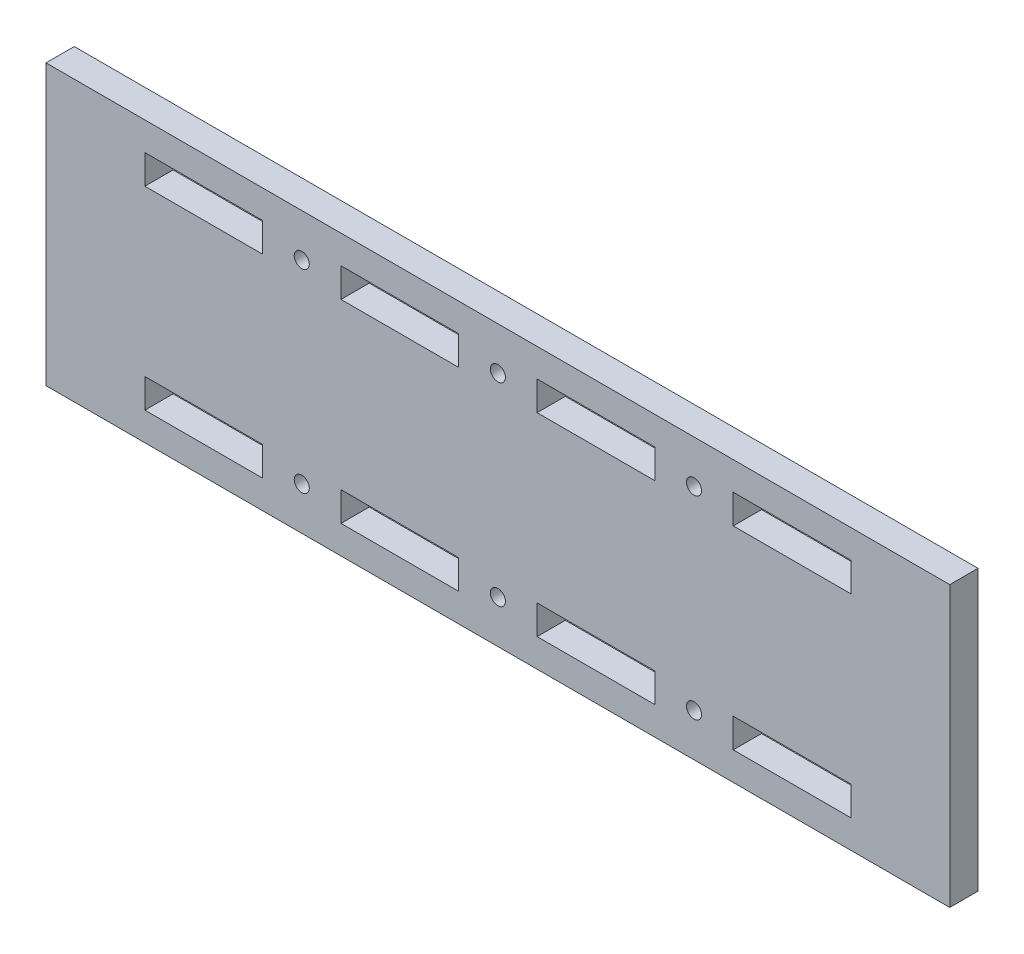
SolidWorks part; units mm, degrees
material "Oak"
ref_plane "Front Plane" through (0, 0, 0) normal (0, 0, 1) x (1, 0, 0)
ref_plane "Top Plane" through (0, 0, 0) normal (0, 1, 0) x (1, 0, 0)
ref_plane "Right Plane" through (0, 0, 0) normal (1, 0, 0) x (0, 0, -1)
sketch "Sketch1" plane through (0, 0, 0) normal (0, 0, 1) x (1, 0, 0)
  line L0 (-33.3333, -17.5) -> (-33.3333, -23.7)
  line L1 (-96, -29.7) -> (96, -29.7)
  line L2 (-96, -29.7) -> (-96, 29.7)
  line L3 (-96, 29.7) -> (96, 29.7)
  line L4 (96, -29.7) -> (96, 29.7)
  line L5 (-96, -29.7) -> (96, 29.7) construction
  line L6 (-96, 29.7) -> (96, -29.7) construction
  line L7 (-75, -17.5) -> (-50, -17.5)
  line L8 (-75, -17.5) -> (-75, -23.7)
  line L9 (-75, -23.7) -> (-50, -23.7)
  line L10 (-50, -17.5) -> (-50, -23.7)
  line L11 (-33.3333, -17.5) -> (-8.3333, -17.5)
  line L12 (-8.3333, -17.5) -> (-8.3333, -23.7)
  line L13 (-33.3333, -23.7) -> (-8.3333, -23.7)
  line L14 (8.3333, -17.5) -> (8.3333, -23.7)
  line L15 (8.3333, -17.5) -> (33.3333, -17.5)
  line L16 (33.3333, -17.5) -> (33.3333, -23.7)
  line L17 (8.3333, -23.7) -> (33.3333, -23.7)
  line L18 (50, -17.5) -> (50, -23.7)
  line L19 (50, -17.5) -> (75, -17.5)
  line L20 (75, -17.5) -> (75, -23.7)
  line L21 (50, -23.7) -> (75, -23.7)
  line L22 (-50, -20.6) -> (-33.3333, -20.6) construction
  line L23 (-8.3333, -20.6) -> (8.3333, -20.6) construction
  line L24 (-75, 23.7) -> (-75, 17.5)
  line L25 (-75, 23.7) -> (-50, 23.7)
  line L26 (-50, 23.7) -> (-50, 17.5)
  line L27 (-75, 17.5) -> (-50, 17.5)
  line L28 (-33.3333, 23.7) -> (-33.3333, 17.5)
  line L29 (-33.3333, 17.5) -> (-8.3333, 17.5)
  line L30 (-8.3333, 23.7) -> (-8.3333, 17.5)
  line L31 (-33.3333, 23.7) -> (-8.3333, 23.7)
  line L32 (8.3333, 23.7) -> (8.3333, 17.5)
  line L33 (8.3333, 17.5) -> (33.3333, 17.5)
  line L34 (33.3333, 23.7) -> (33.3333, 17.5)
  line L35 (8.3333, 23.7) -> (33.3333, 23.7)
  line L36 (50, 23.7) -> (50, 17.5)
  line L37 (50, 17.5) -> (75, 17.5)
  line L38 (75, 23.7) -> (75, 17.5)
  line L39 (50, 23.7) -> (75, 23.7)
  circle A10 centre (-41.6667, -20.6) radius 1.6
  circle A11 centre (0, -20.6) radius 1.6
  circle A12 centre (41.6667, -20.6) radius 1.6
  circle A13 centre (0, 20.6) radius 1.6
  circle A14 centre (41.6667, 20.6) radius 1.6
  circle A15 centre (-41.6667, 20.6) radius 1.6
  point P0 (0, 0)
  point P28 (-50, 20.6)
  dimension "D9" = 3.2
  dimension "D1" = 192
  dimension "D2" = 21
  dimension "D3" = 25
  dimension "D4" = 6
  dimension "D5" = 6.2
  dimension "D6" = 6
  dimension "D7" = 4
  dimension "D8" = 21
  dimension "D12" = 35
  dimension "D11" = 2
  dimension "D10" = 3
  dimension "D13" = 2
extrude "Boss-Extrude1" add sketch "Sketch1" along normal blind 6
